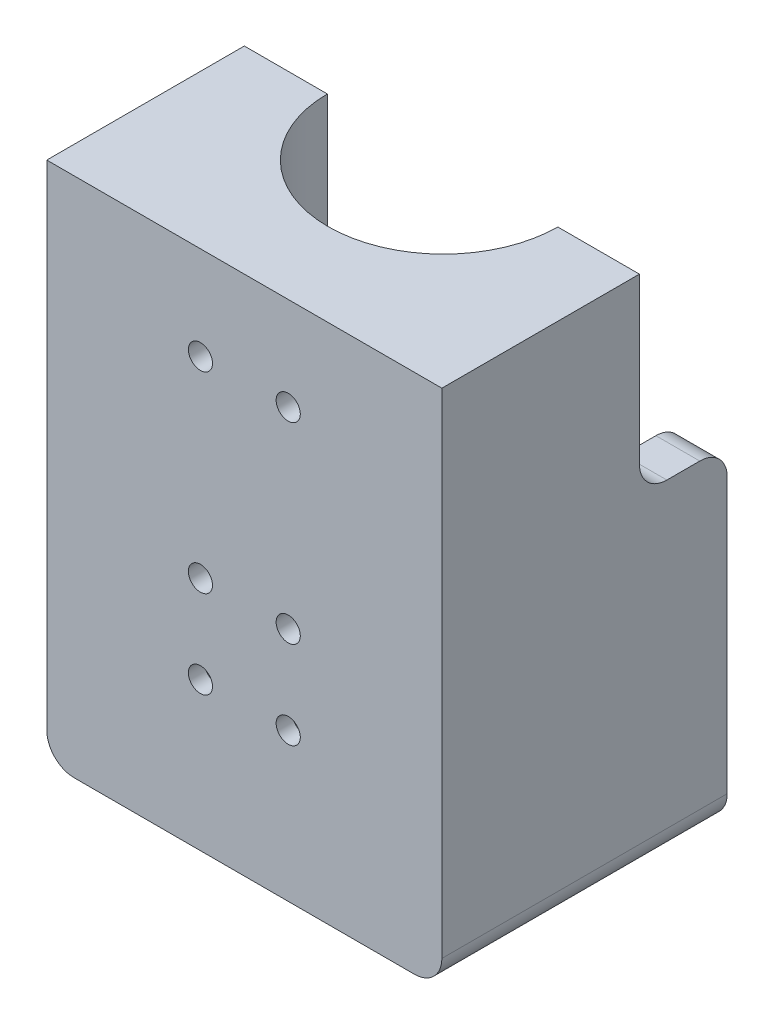
SolidWorks part; units mm, degrees
ref_plane "Front Plane" through (0, 0, 0) normal (0, 0, 1) x (1, 0, 0)
ref_plane "Top Plane" through (0, 0, 0) normal (0, 1, 0) x (1, 0, 0)
ref_plane "Right Plane" through (0, 0, 0) normal (1, 0, 0) x (0, 0, -1)
sketch "Sketch1" plane through (0, 0, 0) normal (0, 1, 0) x (1, 0, 0)
  line L0 (-28, 23.5) -> (-28, -8.5)
  line L1 (-16, -20.5) -> (16, -20.5)
  line L2 (28, 23.5) -> (28, -8.5)
  line L3 (-36, 15.5) -> (-36, -8.5)
  line L4 (-28, 23.5) -> (-36, 23.5)
  line L5 (28, 23.5) -> (36, 23.5)
  line L6 (-16, -28.5) -> (16, -28.5)
  line L7 (36, 15.5) -> (36, -8.5)
  line L8 (-36, 15.5) -> (-36, 23.5)
  line L9 (36, 15.5) -> (36, 23.5)
  line L11 (-36, -28.5) -> (-16, -28.5)
  line L12 (16, -28.5) -> (36, -28.5)
  line L13 (36, -28.5) -> (36, -8.5)
  line L15 (-36, -8.5) -> (-36, -28.5)
  arc A3 (-16, -20.5) -> (-28, -8.5) centre (-16, -8.5) cw
  arc A4 (28, -8.5) -> (16, -20.5) centre (16, -8.5) cw
extrude "Boss-Extrude1" add sketch "Sketch1" along normal blind 50
sketch "Sketch3" plane through (0, 50, 0) normal (0, 1, 0) x (1, 0, 0)
  line L3 (-36, 7.5) -> (-36, -8.5)
  line L6 (-16, -28.5) -> (16, -28.5)
  line L7 (36, 7.5) -> (36, -8.5)
  line L10 (-36, -8.5) -> (-36, -28.5)
  line L11 (21.1284, 7.5) -> (28, 7.5)
  line L12 (-28, 7.5) -> (-20.8708, 7.5)
  line L13 (-28, 7.5) -> (-36, 7.5)
  line L14 (28, 7.5) -> (36, 7.5)
  line L15 (-36, -28.5) -> (-16, -28.5)
  line L16 (16, -28.5) -> (36, -28.5)
  line L17 (36, -28.5) -> (36, -8.5)
  arc A0 (-20.8708, 7.5) -> (21.1284, 7.5) centre (0.1288, 7.6288) ccw
extrude "Boss-Extrude2" add sketch "Sketch3" along normal blind 35 contours L7 L17 L16 L6 L15 L10 L3 L13 L12 A0 L11 L14
sketch "Sketch4" plane through (0, 0, 20.5) normal (0, 0, -1) x (-1, 0, 0)
  circle A0 centre (8, 33) radius 2.2
  circle A1 centre (-8, 33) radius 2.2
  circle A2 centre (-8, 17) radius 2.2
  circle A3 centre (8, 17) radius 2.2
extrude "Cut-Extrude1" cut sketch "Sketch4" against normal blind 35
sketch "Sketch5" plane through (0, 0, 20.5) normal (0, 0, -1) x (-1, 0, 0)
  circle A0 centre (-8, 17) radius 4
  circle A1 centre (8, 17) radius 4
extrude "Cut-Extrude2" cut sketch "Sketch5" against normal blind 5
sketch "Sketch6" plane through (0, 0, 28.5) normal (0, 0, 1) x (1, 0, 0)
  line L0 (-8, 33) -> (-8, 68)
  line L1 (-8, 68) -> (8, 68)
  circle A0 centre (-8, 68) radius 4
  circle A1 centre (8, 68) radius 4
extrude "Cut-Extrude3" cut sketch "Sketch6" against normal blind 34
sketch "Sketch7" plane through (0, 0, 28.5) normal (0, 0, 1) x (1, 0, 0)
  circle A0 centre (-8, 68) radius 4
  circle A1 centre (8, 68) radius 4
  circle A2 centre (8, 68) radius 2.2
  circle A3 centre (-8, 68) radius 2.2
extrude "Boss-Extrude3" add sketch "Sketch7" against normal blind 8
sketch "Sketch8" plane through (0, 0, 0) normal (0, -1, 0) x (1, 0, 0)
  line L1 (-36, 28.5) -> (36, 28.5)
  line L2 (-36, 28.5) -> (-36, -23.5)
  line L3 (-36, -23.5) -> (36, -23.5)
  line L4 (36, 28.5) -> (36, -23.5)
extrude "Boss-Extrude4" add sketch "Sketch8" along normal blind 10
fillet "Fillet1" radius 5 6 edges at (32, 50, -23.5) (-32, 50, -23.5) (-32, 50, -7.5) (32, 50, -7.5) (36, -10, 2.5) (-36, -10, 2.5)
sketch "Sketch9" plane through (0, -10, 0) normal (0, -1, 0) x (1, 0, 0)
  line L0 (-20.8708, -7.5) -> (21.1284, -7.5)
  line L1 (-3.6355, -0.98) -> (3.8931, -0.98)
  line L2 (3.8931, -0.98) -> (7.6575, -7.5)
  line L3 (7.6575, -7.5) -> (3.8931, -14.02)
  line L4 (3.8931, -14.02) -> (-3.6355, -14.02)
  line L5 (-3.6355, -14.02) -> (-7.3998, -7.5)
  line L6 (-7.3998, -7.5) -> (-3.6355, -0.98)
  point P20 (0.1288, -7.5)
  dimension "D1" = 6
extrude "Cut-Extrude5" cut sketch "Sketch9" against normal blind 28 contours L6 L0 L2 L1 | L5 L4 L3 L0
sketch "Sketch11" plane through (0, -10, 0) normal (0, -1, 0) x (-1, 0, 0)
  circle A0 centre (-0.1288, 7.5) radius 4
  circle A1 centre (-0.1288, 7.5) radius 11.1458
extrude "Boss-Extrude6" add sketch "Sketch11" against normal blind 3
